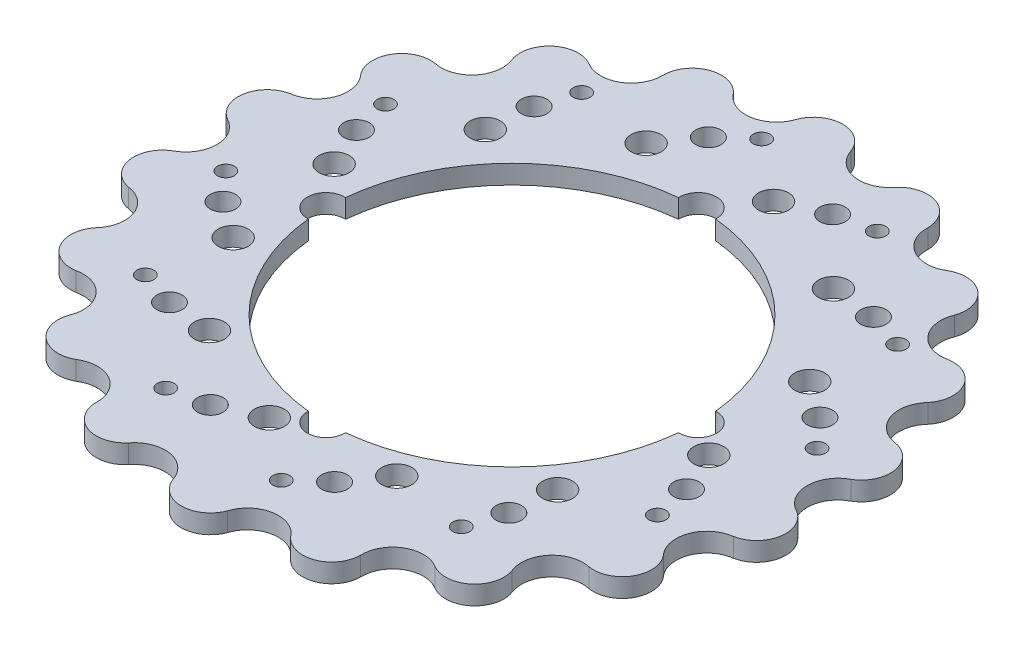
SolidWorks part; units mm, degrees
ref_plane "Front Plane" through (0, 0, 0) normal (0, 0, 1) x (1, 0, 0)
ref_plane "Top Plane" through (0, 0, 0) normal (0, 1, 0) x (1, 0, 0)
ref_plane "Right Plane" through (0, 0, 0) normal (1, 0, 0) x (0, 0, -1)
sketch "Sketch2" plane through (0, 0, 0) normal (0, 1, 0) x (1, 0, 0)
  line L0 (0, 0) -> (0, 88.9) construction
  line L1 (0, 0) -> (30.4056, 83.5387) construction
  line L2 (0, 0) -> (15.4373, 87.5494) construction
  line L3 (0, 0) -> (7.7481, 88.5617) construction
  line L4 (23.009, 85.8708) -> (0, 0) construction
  circle A0 centre (0, 0) radius 88.9
  circle A1 centre (0, 0) radius 79.375
  circle A2 centre (0, 0) radius 84.1375
  arc A3 (0, 88.9) -> (7.3331, 83.8173) centre (0, 81.0687) cw
  arc A4 (7.3331, 83.8173) -> (13.7833, 78.1691) centre (15.22, 86.317) ccw
  arc A5 (21.7764, 81.2706) -> (13.7833, 78.1691) centre (15.22, 86.317) cw
  arc A6 (30.4056, 83.5387) -> (21.7764, 81.2706) centre (27.7271, 76.1797) ccw
  arc A7 (30.4056, 83.5387) -> (35.558, 76.2545) centre (27.7271, 76.1797) cw
  arc A8 (35.558, 76.2545) -> (39.6875, 68.7408) centre (43.8243, 75.9059) ccw
  arc A9 (48.2593, 68.9214) -> (39.6875, 68.7408) centre (43.8243, 75.9059) cw
  arc A10 (57.1438, 68.1014) -> (48.2593, 68.9214) centre (52.11, 62.1023) ccw
  arc A11 (57.1438, 68.1014) -> (59.4942, 59.4942) centre (52.11, 62.1023) cw
  arc A12 (59.4942, 59.4942) -> (60.8048, 51.0213) centre (67.1427, 56.3394) ccw
  arc A13 (68.9214, 48.2593) -> (60.8048, 51.0213) centre (67.1427, 56.3394) cw
  arc A14 (76.9897, 44.45) -> (68.9214, 48.2593) centre (70.2076, 40.5344) ccw
  arc A15 (76.9897, 44.45) -> (76.2545, 35.558) centre (70.2076, 40.5344) cw
  arc A16 (76.2545, 35.558) -> (74.5881, 27.1478) centre (82.3627, 29.9776) ccw
  arc A17 (81.2706, 21.7764) -> (74.5881, 27.1478) centre (82.3627, 29.9776) cw
  arc A18 (87.5494, 15.4373) -> (81.2706, 21.7764) centre (79.8371, 14.0774) ccw
  arc A19 (87.5494, 15.4373) -> (83.8173, 7.3331) centre (79.8371, 14.0774) cw
  arc A20 (83.8173, 7.3331) -> (79.375, 0) centre (87.6486, 0) ccw
  arc A21 (83.8173, -7.3331) -> (79.375, 0) centre (87.6486, 0) cw
  arc A22 (87.5494, -15.4373) -> (83.8173, -7.3331) centre (79.8371, -14.0774) ccw
  arc A23 (87.5494, -15.4373) -> (81.2706, -21.7764) centre (79.8371, -14.0774) cw
  arc A24 (81.2706, -21.7764) -> (74.5881, -27.1478) centre (82.3627, -29.9776) ccw
  arc A25 (76.2545, -35.558) -> (74.5881, -27.1478) centre (82.3627, -29.9776) cw
  arc A26 (76.9897, -44.45) -> (76.2545, -35.558) centre (70.2076, -40.5344) ccw
  arc A27 (76.9897, -44.45) -> (68.9214, -48.2593) centre (70.2076, -40.5344) cw
  arc A28 (68.9214, -48.2593) -> (60.8048, -51.0213) centre (67.1427, -56.3394) ccw
  arc A29 (59.4942, -59.4942) -> (60.8048, -51.0213) centre (67.1427, -56.3394) cw
  arc A30 (57.1438, -68.1014) -> (59.4942, -59.4942) centre (52.11, -62.1023) ccw
  arc A31 (57.1438, -68.1014) -> (48.2593, -68.9214) centre (52.11, -62.1023) cw
  arc A32 (48.2593, -68.9214) -> (39.6875, -68.7408) centre (43.8243, -75.9059) ccw
  arc A33 (35.558, -76.2545) -> (39.6875, -68.7408) centre (43.8243, -75.9059) cw
  arc A34 (30.4056, -83.5387) -> (35.558, -76.2545) centre (27.7271, -76.1797) ccw
  arc A35 (30.4056, -83.5387) -> (21.7764, -81.2706) centre (27.7271, -76.1797) cw
  arc A36 (21.7764, -81.2706) -> (13.7833, -78.1691) centre (15.22, -86.317) ccw
  arc A37 (7.3331, -83.8173) -> (13.7833, -78.1691) centre (15.22, -86.317) cw
  arc A38 (0, -88.9) -> (7.3331, -83.8173) centre (0, -81.0687) ccw
  arc A39 (0, -88.9) -> (-7.3331, -83.8173) centre (0, -81.0687) cw
  arc A40 (-7.3331, -83.8173) -> (-13.7833, -78.1691) centre (-15.22, -86.317) ccw
  arc A41 (-21.7764, -81.2706) -> (-13.7833, -78.1691) centre (-15.22, -86.317) cw
  arc A42 (-30.4056, -83.5387) -> (-21.7764, -81.2706) centre (-27.7271, -76.1797) ccw
  arc A43 (-30.4056, -83.5387) -> (-35.558, -76.2545) centre (-27.7271, -76.1797) cw
  arc A44 (-35.558, -76.2545) -> (-39.6875, -68.7408) centre (-43.8243, -75.9059) ccw
  arc A45 (-48.2593, -68.9214) -> (-39.6875, -68.7408) centre (-43.8243, -75.9059) cw
  arc A46 (-57.1438, -68.1014) -> (-48.2593, -68.9214) centre (-52.11, -62.1023) ccw
  arc A47 (-57.1438, -68.1014) -> (-59.4942, -59.4942) centre (-52.11, -62.1023) cw
  arc A48 (-59.4942, -59.4942) -> (-60.8048, -51.0213) centre (-67.1427, -56.3394) ccw
  arc A49 (-68.9214, -48.2593) -> (-60.8048, -51.0213) centre (-67.1427, -56.3394) cw
  arc A50 (-76.9897, -44.45) -> (-68.9214, -48.2593) centre (-70.2076, -40.5344) ccw
  arc A51 (-76.9897, -44.45) -> (-76.2545, -35.558) centre (-70.2076, -40.5344) cw
  arc A52 (-76.2545, -35.558) -> (-74.5881, -27.1478) centre (-82.3627, -29.9776) ccw
  arc A53 (-81.2706, -21.7764) -> (-74.5881, -27.1478) centre (-82.3627, -29.9776) cw
  arc A54 (-87.5494, -15.4373) -> (-81.2706, -21.7764) centre (-79.8371, -14.0774) ccw
  arc A55 (-87.5494, -15.4373) -> (-83.8173, -7.3331) centre (-79.8371, -14.0774) cw
  arc A56 (-83.8173, -7.3331) -> (-79.375, 0) centre (-87.6486, 0) ccw
  arc A57 (-83.8173, 7.3331) -> (-79.375, 0) centre (-87.6486, 0) cw
  arc A58 (-87.5494, 15.4373) -> (-83.8173, 7.3331) centre (-79.8371, 14.0774) ccw
  arc A59 (-87.5494, 15.4373) -> (-81.2706, 21.7764) centre (-79.8371, 14.0774) cw
  arc A60 (-81.2706, 21.7764) -> (-74.5881, 27.1478) centre (-82.3627, 29.9776) ccw
  arc A61 (-76.2545, 35.558) -> (-74.5881, 27.1478) centre (-82.3627, 29.9776) cw
  arc A62 (-76.9897, 44.45) -> (-76.2545, 35.558) centre (-70.2076, 40.5344) ccw
  arc A63 (-76.9897, 44.45) -> (-68.9214, 48.2593) centre (-70.2076, 40.5344) cw
  arc A64 (-68.9214, 48.2593) -> (-60.8048, 51.0213) centre (-67.1427, 56.3394) ccw
  arc A65 (-59.4942, 59.4942) -> (-60.8048, 51.0213) centre (-67.1427, 56.3394) cw
  arc A66 (-57.1438, 68.1014) -> (-59.4942, 59.4942) centre (-52.11, 62.1023) ccw
  arc A67 (-57.1438, 68.1014) -> (-48.2593, 68.9214) centre (-52.11, 62.1023) cw
  arc A68 (-48.2593, 68.9214) -> (-39.6875, 68.7408) centre (-43.8243, 75.9059) ccw
  arc A69 (-35.558, 76.2545) -> (-39.6875, 68.7408) centre (-43.8243, 75.9059) cw
  arc A70 (-30.4056, 83.5387) -> (-35.558, 76.2545) centre (-27.7271, 76.1797) ccw
  arc A71 (-30.4056, 83.5387) -> (-21.7764, 81.2706) centre (-27.7271, 76.1797) cw
  arc A72 (-21.7764, 81.2706) -> (-13.7833, 78.1691) centre (-15.22, 86.317) ccw
  arc A73 (-7.3331, 83.8173) -> (-13.7833, 78.1691) centre (-15.22, 86.317) cw
  arc A74 (0, 88.9) -> (-7.3331, 83.8173) centre (0, 81.0687) ccw
  point P10 (7.3331, 83.8173)
  point P11 (21.7764, 81.2706)
  point P12 (13.7833, 78.1691)
  point P175 (0, 0)
  dimension "D1" = 177.8
  dimension "D2" = 158.75
  dimension "D5" = 168.275
  dimension "D4" = 18
  dimension "D3" = 20
  dimension "D6" = 5
  dimension "D7" = 5
extrude "Boss-Extrude1" add sketch "Sketch2" along normal blind 5.08 contours A67 A66 A2 | A68 A2 A65 A1 | A71 A70 A2 | A72 A2 A69 A1 | A2 A73 A1 A4 | A3 A74 A2 | A8 A2 A5 A1 | A7 A6 A2 | A11 A10 A2 | A12 A2 A9 A1 | A16 A2 A13 A1 | A15 A14 A2 | A20 A2 A17 A1 | A19 A18 A2 | A24 A2 A21 A1 | A23 A22 A2 | A28 A2 A25 A1 | A27 A26 A2 | A32 A2 A29 A1 | A31 A30 A2 | A36 A2 A33 A1 | A35 A34 A2 | A40 A2 A37 A1 | A39 A38 A2 | A44 A2 A41 A1 | A43 A42 A2 | A48 A2 A45 A1 | A47 A46 A2 | A52 A2 A49 A1 | A51 A50 A2 | A1 | A55 A54 A2 | A59 A58 A2 | A63 A62 A2 | A64 A2 A61 A1 | A60 A2 A57 A1 | A56 A2 A53 A1
sketch "Sketch3" plane through (0, 5.08, 0) normal (0, 1, 0) x (1, 0, 0)
  circle A0 centre (0, 0) radius 50
  circle A1 centre (0, 50) radius 5
  circle A2 centre (50, 0) radius 5
  circle A3 centre (0, -50) radius 5
  circle A4 centre (-50, 0) radius 5
  point P13 (0, 0)
  dimension "D1" = 4
  dimension "D2" = 10
extrude "Cut-Extrude1" cut sketch "Sketch3" against normal through all contours A0 A1 | A0 A1 | A0 A4 | A0 A4 | A0 A2 | A0 A2 | A0 A3 | A0 A3
sketch "Sketch4" plane through (0, 5.08, 0) normal (0, 1, 0) x (1, 0, 0)
  arc A0 (0, 55) -> (39.6875, 68.7408) centre (35.1097, 17.7778) cw construction
  arc A1 (4.9937, 49.75) -> (-4.9937, 49.75) centre (0, 50) ccw construction
  arc A2 (35.558, 76.2545) -> (48.2593, 68.9214) centre (43.8243, 75.9059) ccw construction
  circle A3 centre (8.7092, 61.6093) radius 4.0351
  circle A4 centre (19.6365, 66.5504) radius 3.4245
  circle A5 centre (29.5538, 68.6434) radius 2.2596
  circle A6 centre (37.077, 49.3409) radius 4.0351
  circle A7 centre (49.0109, 48.1563) radius 3.4245
  circle A8 centre (58.646, 45.0104) radius 2.2596
  circle A9 centre (55.5101, 24.5322) radius 4.0351
  circle A10 centre (65.2529, 17.5394) radius 3.4245
  circle A11 centre (72.0241, 9.9974) radius 2.2596
  circle A12 centre (59.0693, -6.1692) radius 4.0351
  circle A13 centre (64.0104, -17.0965) radius 3.4245
  circle A14 centre (66.1034, -27.0138) radius 2.2596
  circle A15 centre (46.8009, -34.537) radius 4.0351
  circle A16 centre (45.6163, -46.4709) radius 3.4245
  circle A17 centre (42.4704, -56.106) radius 2.2596
  circle A18 centre (21.9922, -52.9701) radius 4.0351
  circle A19 centre (14.9994, -62.7129) radius 3.4245
  circle A20 centre (7.4574, -69.4841) radius 2.2596
  circle A21 centre (-8.7092, -56.5293) radius 4.0351
  circle A22 centre (-19.6365, -61.4704) radius 3.4245
  circle A23 centre (-29.5538, -63.5634) radius 2.2596
  circle A24 centre (-37.077, -44.2609) radius 4.0351
  circle A25 centre (-49.0109, -43.0763) radius 3.4245
  circle A26 centre (-58.646, -39.9304) radius 2.2596
  circle A27 centre (-55.5101, -19.4522) radius 4.0351
  circle A28 centre (-65.2529, -12.4594) radius 3.4245
  circle A29 centre (-72.0241, -4.9174) radius 2.2596
  circle A30 centre (-59.0693, 11.2492) radius 4.0351
  circle A31 centre (-64.0104, 22.1765) radius 3.4245
  circle A32 centre (-66.1034, 32.0938) radius 2.2596
  circle A33 centre (-46.8009, 39.617) radius 4.0351
  circle A34 centre (-45.6163, 51.5509) radius 3.4245
  circle A35 centre (-42.4704, 61.186) radius 2.2596
  circle A36 centre (-21.9922, 58.0501) radius 4.0351
  circle A37 centre (-14.9994, 67.7929) radius 3.4245
  circle A38 centre (-7.4574, 74.5641) radius 2.2596
  point P16 (29.5433, 68.7408)
  point P17 (18.359, 66.1589)
  point P83 (0, 2.54)
  point P84 (19.1237, 66.4169)
  point P85 (19.6365, 66.5504)
  dimension "D1" = 12
extrude "Cut-Extrude3" cut sketch "Sketch4" against normal through all
